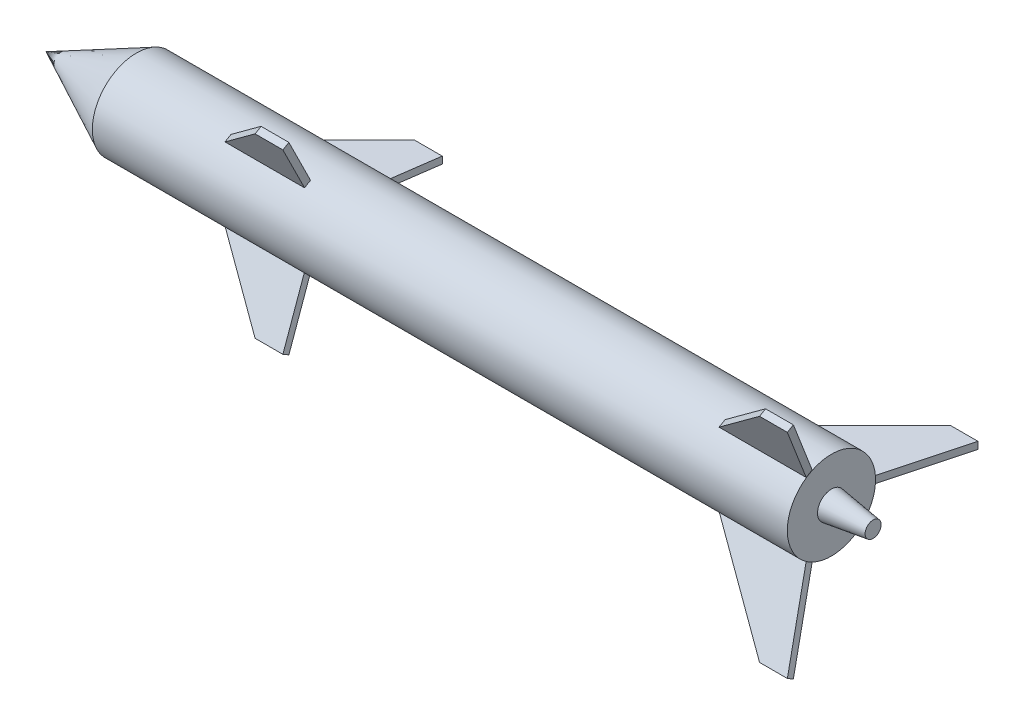
SolidWorks part; units mm, degrees
ref_plane "Plano frontal" through (0, 0, 0) normal (0, 0, 1) x (1, 0, 0)
ref_plane "Plano superior" through (0, 0, 0) normal (0, 1, 0) x (1, 0, 0)
ref_plane "Plano direito" through (0, 0, 0) normal (1, 0, 0) x (0, 0, -1)
sketch "Esboço1" plane through (0, 0, 0) normal (0, 0, 1) x (1, 0, 0)
  line L0 (-90.3495, 0) -> (121.6133, 0) construction
  line L1 (0, 0) -> (26.0389, 12.7)
  line L2 (26.0389, 12.7) -> (226.0389, 12.7)
  line L3 (226.0389, 12.7) -> (226.0389, 0)
  line L4 (0, 0) -> (226.0389, 0)
  dimension "D1" = 26
  dimension "D2" = 25.4
  dimension "D3" = 200
revolve "Revolução1" add sketch "Esboço1" angle 360 about L0
sketch "Esboço2" plane through (0, 0, 0) normal (0, 1, 0) x (1, 0, 0)
  line L0 (-12.7863, 0) -> (246.5894, 0) construction
  line L1 (26.0389, -12.7) -> (26.0389, 12.7) construction
  line L2 (76.0389, 30) -> (84.0389, 30)
  line L3 (46.0389, 0) -> (76.0389, 30)
  line L4 (84.0389, 0) -> (84.0389, 30) construction
  line L5 (84.0389, 30) -> (79.8226, 0)
  line L6 (46.0389, 0) -> (79.8226, 0)
  dimension "D1" = 8
  dimension "D2" = 8
  dimension "D3" = 45
  dimension "D4" = 20
  dimension "D5" = 30
sketch "Esboço3" plane through (0, 0, 0) normal (0, 1, 0) x (1, 0, 0)
  line L0 (222.5789, 0) -> (232.225, 36)
  line L1 (226.0389, 0) -> (26.0389, 0) construction
  line L3 (226.0389, -12.7) -> (226.0389, 12.7) construction
  line L4 (232.225, 36) -> (224.225, 36)
  line L5 (224.225, 36) -> (188.225, 0)
  line L6 (-18.9182, 0) -> (316.9456, 0) construction
  line L7 (26.0389, -12.7) -> (26.0389, 12.7) construction
  line L8 (188.225, 0) -> (222.5789, 0)
  dimension "D1" = 15
  dimension "D2" = 3.46
  dimension "D3" = 36
  dimension "D4" = 45
  dimension "D5" = 8
extrude "Ressalto-extrusão2" add sketch "Esboço3" along normal mid plane 2
extrude "Ressalto-extrusão3" add sketch "Esboço2" along normal mid plane 2
pattern_circular "PadrãoCircular2" count 3 over 360 about axis through (0, 0, 0) along (1, 0, 0) of "Ressalto-extrusão3", "Ressalto-extrusão2"
sketch "Esboço4" plane through (226.0389, 0, 0) normal (1, 0, 0) x (0, 0, -1)
  circle A0 centre (0, 0) radius 4
  dimension "D1" = 8
extrude "Ressalto-extrusão4" add sketch "Esboço4" along normal blind 12 draft 8
